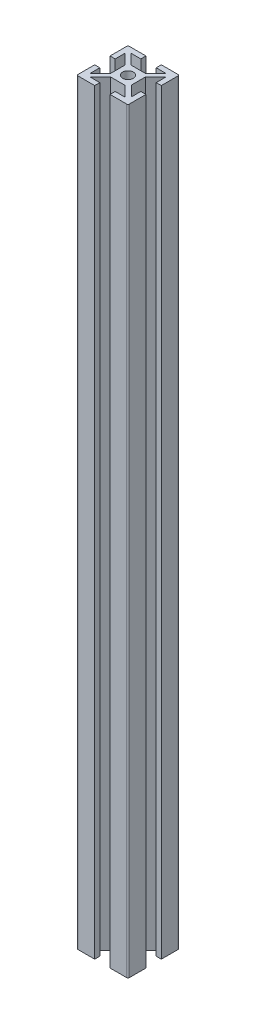
SolidWorks part; units mm, degrees
material "6061 Alloy"
ref_plane "Front Plane" through (0, 0, 0) normal (0, 0, 1) x (1, 0, 0)
ref_plane "Top Plane" through (0, 0, 0) normal (0, 1, 0) x (1, 0, 0)
ref_plane "Right Plane" through (0, 0, 0) normal (1, 0, 0) x (0, 0, -1)
ref_plane "Plane1" through (0, 295, 0) normal (0, 1, 0) x (1, 0, 0)
sketch "Sketch1" plane through (0, 295, 0) normal (0, 1, 0) x (1, 0, 0)
  line L0 (4, 2.7464) -> (8, 6.7464)
  line L1 (8, 6.7464) -> (8, 3)
  line L2 (8, 3) -> (10, 3)
  line L3 (10, 3) -> (10, 9.5)
  line L4 (9.5, 10) -> (3, 10)
  line L5 (3, 10) -> (3, 8)
  line L6 (3, 8) -> (6.8633, 8)
  line L7 (6.8633, 8) -> (2.8633, 4)
  line L8 (2.8633, 4) -> (-2.75, 4)
  line L9 (-2.75, 4) -> (-6.75, 8)
  line L10 (-6.75, 8) -> (-3, 8)
  line L11 (-3, 8) -> (-3, 10)
  line L12 (-3, 10) -> (-9.5, 10)
  line L13 (-10, 9.5) -> (-10, 3)
  line L14 (-10, 3) -> (-8, 3)
  line L15 (-8, 3) -> (-8, 6.75)
  line L16 (-8, 6.75) -> (-4, 2.75)
  line L17 (-4, 2.75) -> (-4, -2.75)
  line L18 (-4, -2.75) -> (-8, -6.75)
  line L19 (-8, -6.75) -> (-8, -3)
  line L20 (-8, -3) -> (-10, -3)
  line L21 (-10, -3) -> (-10, -9.5)
  line L22 (-9.5, -10) -> (-3, -10)
  line L23 (-3, -10) -> (-3, -8)
  line L24 (-3, -8) -> (-6.75, -8)
  line L25 (-6.75, -8) -> (-2.75, -4)
  line L26 (-2.75, -4) -> (2.8685, -4)
  line L27 (2.8685, -4) -> (6.8685, -8)
  line L28 (6.8685, -8) -> (3, -8)
  line L29 (3, -8) -> (3, -10)
  line L30 (3, -10) -> (9.5, -10)
  line L31 (10, -9.5) -> (10, -3)
  line L32 (10, -3) -> (8, -3)
  line L33 (8, -3) -> (8, -6.6652)
  line L34 (8, -6.6652) -> (4, -2.6652)
  line L35 (4, -2.6652) -> (4, 2.7464)
  arc A0 (10, 9.5) -> (9.5, 10) centre (9.5, 9.5) ccw
  arc A1 (-9.5, 10) -> (-10, 9.5) centre (-9.5, 9.5) ccw
  arc A2 (-10, -9.5) -> (-9.5, -10) centre (-9.5, -9.5) ccw
  arc A3 (9.5, -10) -> (10, -9.5) centre (9.5, -9.5) ccw
  circle A4 centre (0, 0) radius 2.1
extrude "Boss-Extrude1" add sketch "Sketch1" against normal blind 295
ref_plane "Plane2" through (0, 0, 0) normal (1, 0, 0) x (0, 0, -1)
ref_plane "Plane4" through (0, 0, 0) normal (0, 0, -1) x (-1, 0, 0)
ref_plane "Plane5" through (0, 147.5, 0) normal (0, 1, 0) x (1, 0, 0)
